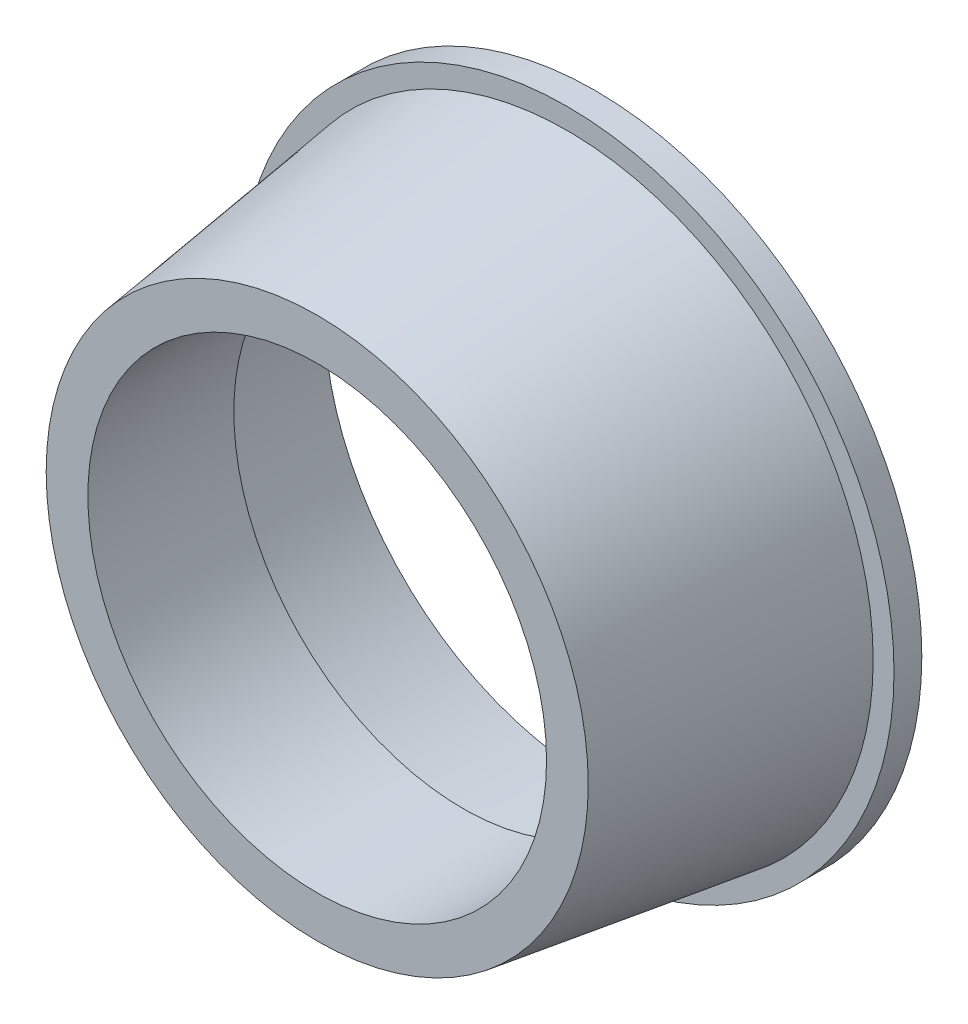
SolidWorks part; units mm, degrees
ref_plane "Front Plane" through (0, 0, 0) normal (1, 0, 0) x (0, 1, 0)
ref_plane "Top Plane" through (0, 0, 0) normal (0, 0, 1) x (0, 1, 0)
ref_plane "Right Plane" through (0, 0, 0) normal (0, 1, 0) x (-1, 0, 0)
sketch "Sketch1" plane through (0, 0, 0) normal (0, 1, 0) x (-1, 0, 0)
  line L0 (19.5, 0) -> (19.25, 8)
  line L1 (19.25, 8) -> (16.5, 9.5)
  line L2 (16.5, 9.5) -> (16.5, 20)
  line L3 (16.5, 20) -> (0, 20) construction
  line L4 (0, 20) -> (0, 0) construction
  line L5 (0, 0) -> (19.5, 0) construction
  line L8 (23.5, 0) -> (19.5, 0)
  line L9 (23.5, 0) -> (23.5, 2)
  line L10 (23.5, 2) -> (22, 2)
  line L11 (22, 2) -> (19.5, 20)
  line L12 (19.5, 20) -> (16.5, 20)
  dimension "D1" = 19.5
  dimension "D2" = 8
  dimension "D3" = 19.25
  dimension "D4" = 16.5
  dimension "D5" = 9.5
  dimension "D6" = 20
  dimension "D7" = 16.5
  dimension "D8" = 4
  dimension "D9" = 2
  dimension "D10" = 22
  dimension "D11" = 19.5
revolve "Revolve1" add sketch "Sketch1" angle 360 about L4
